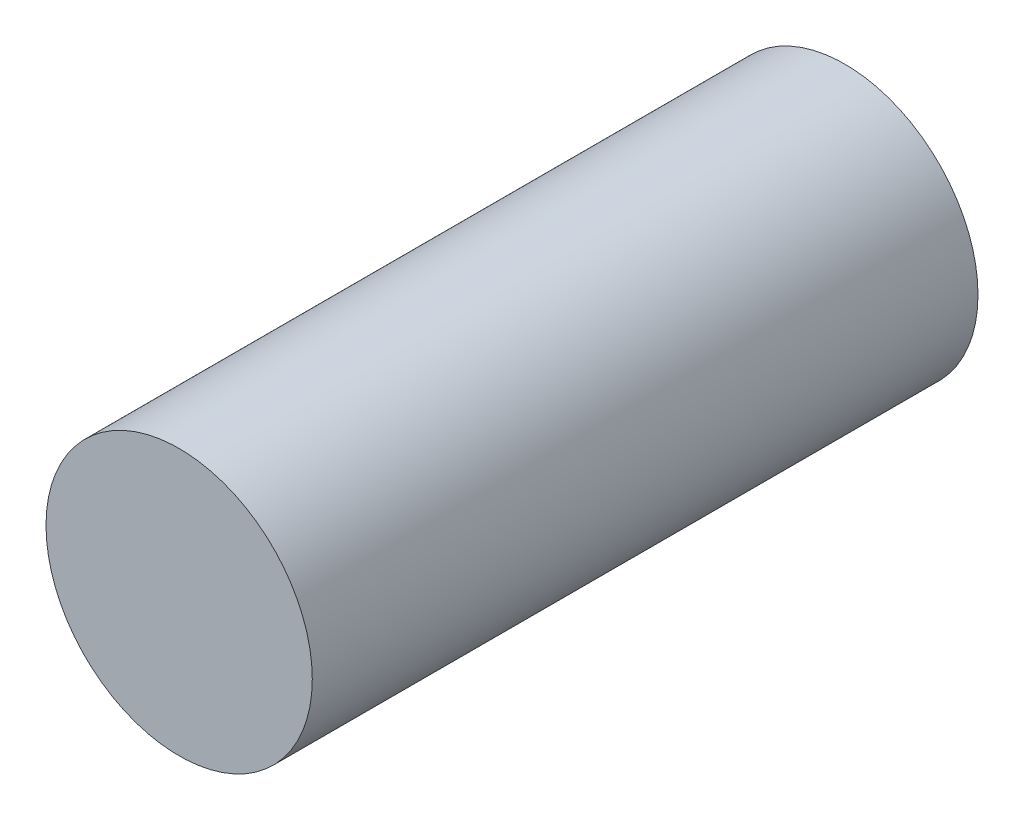
SolidWorks part; units mm, degrees
ref_plane "前视基准面" through (0, 0, 0) normal (0, 0, 1) x (1, 0, 0)
ref_plane "上视基准面" through (0, 0, 0) normal (0, 1, 0) x (1, 0, 0)
ref_plane "右视基准面" through (0, 0, 0) normal (1, 0, 0) x (0, 0, -1)
other "Configuration Table"
sketch "草图1" plane through (0, 0, 0) normal (0, 0, 1) x (1, 0, 0)
  circle A0 centre (0, 0) radius 3
  dimension "diameter" = 6
extrude "Shank" add sketch "草图1" along normal blind 15
